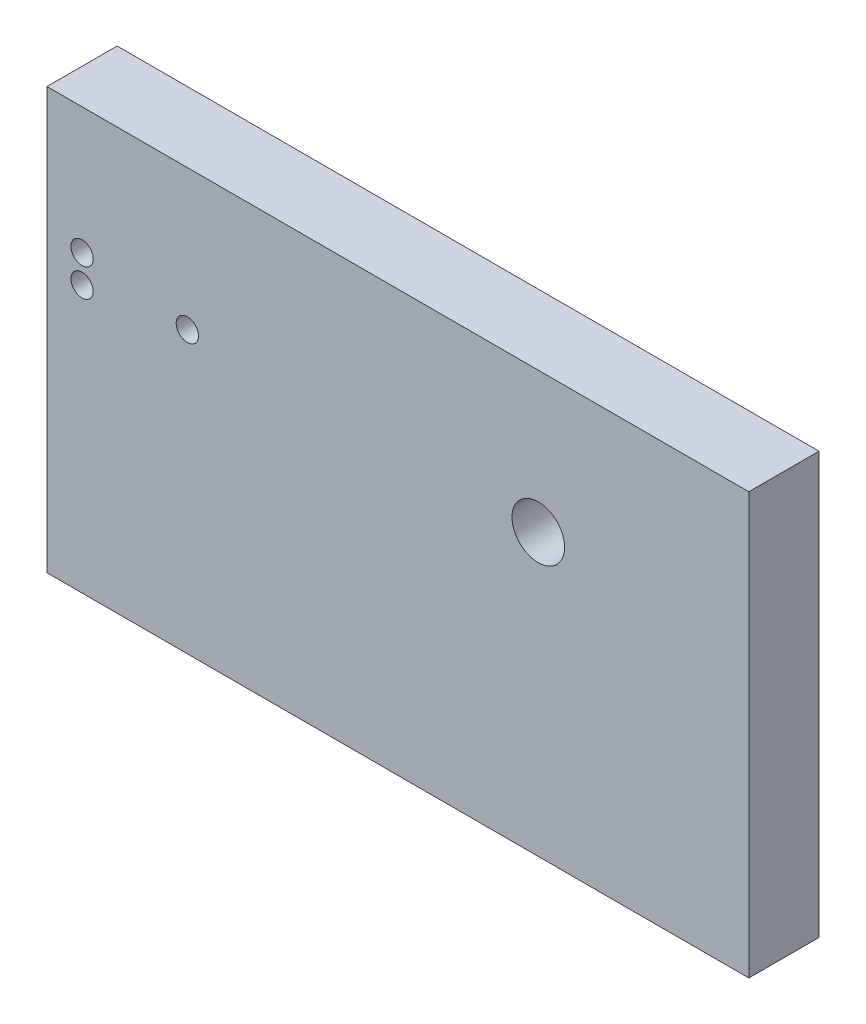
SolidWorks part; units mm, degrees
ref_plane "Front Plane" through (0, 0, 0) normal (0, 0, 1) x (1, 0, 0)
ref_plane "Top Plane" through (0, 0, 0) normal (0, 1, 0) x (1, 0, 0)
ref_plane "Right Plane" through (0, 0, 0) normal (1, 0, 0) x (0, 0, -1)
sketch "Sketch1" plane through (0, 0, 0) normal (0, 0, 1) x (1, 0, 0)
  line L1 (0, 0) -> (127, 0)
  line L2 (0, 0) -> (0, 76.2)
  line L3 (0, 76.2) -> (127, 76.2)
  line L4 (127, 0) -> (127, 76.2)
  dimension "D1" = 127
  dimension "D2" = 76.2
extrude "Boss-Extrude1" add sketch "Sketch1" along normal blind 12.7 contours L2 L1 L4 L3
hole_wizard "1/32 (0.159) Diameter Hole1" positions "Sketch5" profile "Sketch6" hole size "1/32" standard "ANSI Inch" end condition through all
sketch "Sketch5" plane through (0, 0, 12.7) normal (0, 0, 1) x (1, 0, 0)
  line L0 (0, 0) -> (0, 76.2) construction
  line L1 (0, 0) -> (127, 0) construction
  point P0 (25.4, 50.8)
  dimension "D1" = 25.4
  dimension "D2" = 50.8
sketch "Sketch6" plane through (25.4, 50.8, 12.7) normal (1, 0, 0) x (0, -1, 0)
  line L0 (0, 0) -> (0, 12.7)
  line L1 (0, 12.7) -> (2.0193, 12.7)
  line L2 (2.0193, 12.7) -> (2.0193, 0)
  line L5 (2.0193, 0) -> (0, 0)
  line L11 (0, -6.35) -> (0, 107.95) construction
  dimension "Thru Hole Dia." = 4.0386
  dimension "Thru Hole Depth" = 12.7
hole_wizard "#10-32 Tapped Hole1" positions "Sketch9" profile "Sketch10" tap size "#10-32" standard "ANSI Inch"
sketch "Sketch9" plane through (0, 0, 0) normal (0, -1, 0) x (-1, 0, 0)
  line L0 (0, -12.7) -> (-127, -12.7) construction
  line L1 (-19.05, -6.35) -> (-107.95, -6.35) construction
  line L3 (-63.5, -12.7) -> (-63.5, 0) construction
  line L4 (0, 0) -> (-127, 0) construction
  point P0 (-19.05, -6.35)
  point P2 (-107.95, -6.35)
  point P21 (-63.5, -6.35)
  dimension "D1" = 6.35
  dimension "D2" = 88.9
sketch "Sketch10" plane through (19.05, 0, 6.35) normal (1, 0, 0) x (0, 0, -1)
  line L0 (0, 0) -> (0, 12.7)
  line L1 (0, 12.7) -> (2.0193, 11.4867)
  line L2 (2.0193, 11.4867) -> (2.0193, 0)
  line L5 (2.0193, 0) -> (0, 0)
  line L10 (0, 12.7) -> (-2.0193, 11.4867) construction
  line L11 (0, -6.35) -> (0, 107.95) construction
  dimension "Tap Drill Dia." = 4.0386
  dimension "Tap Drill Depth" = 12.7
  dimension "Drill Angle" = 118
cosmetic thread "Hole Thread3" parameters "D1"=12.7, "D2"=4.826
cosmetic thread "Hole Thread4" parameters "D1"=12.7, "D2"=4.826
hole_wizard "3/8 (0.375) Diameter Hole1" positions "Sketch14" profile "Sketch15" hole size "3/8" standard "ANSI Inch" end condition through all
sketch "Sketch14" plane through (0, 0, 12.7) normal (0, 0, 1) x (1, 0, 0)
  line L0 (0, 0) -> (127, 0) construction
  line L1 (0, 0) -> (0, 76.2) construction
  point P0 (88.9, 50.8)
  dimension "D1" = 50.8
  dimension "D2" = 88.9
sketch "Sketch15" plane through (88.9, 50.8, 12.7) normal (1, 0, 0) x (0, -1, 0)
  line L0 (0, 0) -> (0, 12.7)
  line L1 (0, 12.7) -> (4.7625, 12.7)
  line L2 (4.7625, 12.7) -> (4.7625, 0)
  line L5 (4.7625, 0) -> (0, 0)
  line L11 (0, -6.35) -> (0, 107.95) construction
  dimension "Thru Hole Dia." = 9.525
  dimension "Thru Hole Depth" = 12.7
hole_wizard "#10-32 Tapped Hole2" positions "Sketch16" profile "Sketch17" tap size "#10-32" standard "ANSI Inch"
sketch "Sketch16" plane through (0, 0, 12.7) normal (0, 0, 1) x (1, 0, 0)
  line L0 (0, 0) -> (0, 76.2) construction
  line L1 (0, 0) -> (127, 0) construction
  point P0 (6.35, 48.26)
  dimension "D1" = 6.35
  dimension "D2" = 48.26
sketch "Sketch17" plane through (6.35, 48.26, 12.7) normal (1, 0, 0) x (0, -1, 0)
  line L0 (0, 0) -> (0, 15.6913)
  line L1 (0, 15.6913) -> (2.0193, 14.478)
  line L2 (2.0193, 14.478) -> (2.0193, 0)
  line L5 (2.0193, 0) -> (0, 0)
  line L10 (0, 15.6913) -> (-2.0193, 14.478) construction
  line L11 (0, -6.35) -> (0, 107.95) construction
  dimension "Tap Drill Dia." = 4.0386
  dimension "Tap Drill Depth" = 14.478
  dimension "Drill Angle" = 118
cosmetic thread "Hole Thread5" parameters "D1"=9.652, "D2"=4.826
hole_wizard "#21 (0.159) Diameter Hole1" positions "Sketch18" profile "Sketch19" hole size "#21" standard "ANSI Inch"
sketch "Sketch18" plane through (0, 0, 12.7) normal (0, 0, 1) x (1, 0, 0)
  line L0 (0, 0) -> (0, 76.2) construction
  line L1 (0, 0) -> (127, 0) construction
  point P0 (6.35, 53.34)
  dimension "D1" = 6.35
  dimension "D2" = 53.34
sketch "Sketch19" plane through (6.35, 53.34, 12.7) normal (1, 0, 0) x (0, -1, 0)
  line L0 (0, 0) -> (0, 15.6913)
  line L1 (0, 15.6913) -> (2.0193, 14.478)
  line L2 (2.0193, 14.478) -> (2.0193, 0)
  line L5 (2.0193, 0) -> (0, 0)
  line L10 (0, 15.6913) -> (-2.0193, 14.478) construction
  line L11 (0, -6.35) -> (0, 107.95) construction
  dimension "Hole Dia." = 4.0386
  dimension "Hole Depth" = 14.478
  dimension "Drill Angle" = 118
